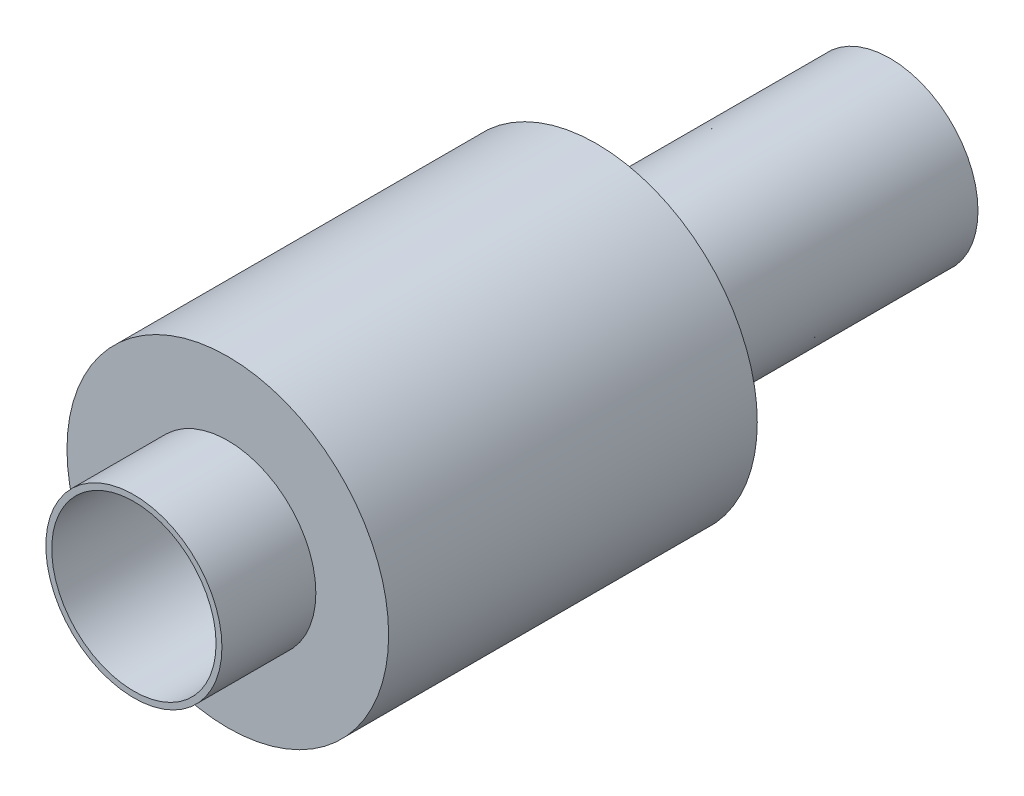
SolidWorks part; units mm, degrees
material "6061-T6 (SS)"
ref_plane "X-Y Datum" through (0, 0, 0) normal (0, 0, 1) x (1, 0, 0)
ref_plane "X-Z Datum" through (0, 0, 0) normal (0, 1, 0) x (1, 0, 0)
ref_plane "Y-Z Datum" through (0, 0, 0) normal (1, 0, 0) x (0, 0, -1)
sketch "Sketch1" plane through (0, 0, 0) normal (0, 0, 1) x (1, 0, 0)
  circle A0 centre (0, 0) radius 17.399
  dimension "D1" = 34.798
extrude "Boss-Extrude1" add sketch "Sketch1" along normal blind 50.038
sketch "Sketch3" plane through (0, 0, 50.038) normal (0, 0, 1) x (1, 0, 0)
  circle A0 centre (0, 0) radius 9.525
  circle A1 centre (0, 0) radius 38.1
  dimension "D1" = 76.2
  dimension "D2" = 19.05
extrude "Cut-Extrude1" cut sketch "Sketch3" against normal blind 10.16
sketch "Sketch4" plane through (0, 0, 50.038) normal (0, 0, 1) x (1, 0, 0)
  circle A0 centre (0, 0) radius 8.89
  dimension "D1" = 17.78
extrude "Cut-Extrude2" cut sketch "Sketch4" against normal blind 127
sketch "Sketch5" plane through (0, 0, 0) normal (0, 0, -1) x (-1, 0, 0)
  circle A0 centre (0, 0) radius 9.525
  circle A1 centre (0, 0) radius 8.89
  dimension "D1" = 17.78
  dimension "D2" = 19.05
extrude "Boss-Extrude2" add sketch "Sketch5" along normal blind 31.75
